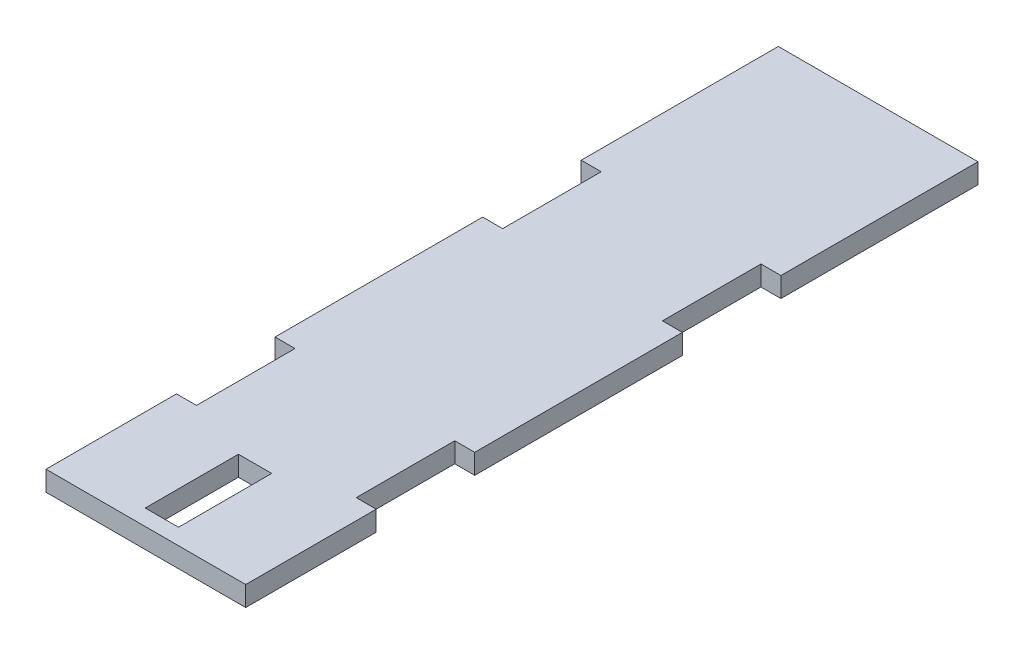
SolidWorks part; units mm, degrees
ref_plane "Спереди" through (0, 0, 0) normal (0, 0, 1) x (1, 0, 0)
ref_plane "Сверху" through (0, 0, 0) normal (0, 1, 0) x (1, 0, 0)
ref_plane "Справа" through (0, 0, 0) normal (1, 0, 0) x (0, 0, -1)
other "Configuration Table"
sketch "Эскиз1" plane through (0, 0, 0) normal (0, 1, 0) x (1, 0, 0)
  line L0 (-8.7681, 0) -> (8.7681, 0) construction
  line L1 (-15, -50) -> (15, -50)
  line L2 (-15, -50) -> (-15, -30.3972)
  line L3 (-15, 50) -> (15, 50)
  line L4 (15, -50) -> (15, -30.3972)
  line L5 (-15, -50) -> (15, 50) construction
  line L6 (-15, 50) -> (15, -50) construction
  line L7 (-15, 30.3972) -> (-12, 30.3972)
  line L9 (-15, 15.5972) -> (-12, 15.5972)
  line L10 (-12, 30.3972) -> (-12, 15.5972)
  line L11 (0, -13.162) -> (0, 13.162) construction
  line L12 (12, 30.3972) -> (12, 15.5972)
  line L13 (15, 15.5972) -> (12, 15.5972)
  line L15 (15, 30.3972) -> (12, 30.3972)
  line L16 (15, -30.3972) -> (12, -30.3972)
  line L18 (15, -15.5972) -> (12, -15.5972)
  line L19 (12, -30.3972) -> (12, -15.5972)
  line L20 (-12, -30.3972) -> (-12, -15.5972)
  line L21 (-15, -15.5972) -> (-12, -15.5972)
  line L23 (-15, -30.3972) -> (-12, -30.3972)
  line L24 (-15, 30.3972) -> (-15, 50)
  line L25 (15, 30.3972) -> (15, 50)
  line L26 (15, -15.5972) -> (15, 15.5972)
  line L27 (-15, -15.5972) -> (-15, 15.5972)
  point P0 (0, 0)
  point P13 (0, 0)
  point P16 (0, 0)
  dimension "D1" = 100
  dimension "D2" = 30
  dimension "D3" = 14.8
  dimension "D4" = 3
extrude "Бобышка-Вытянуть1" add sketch "Эскиз1" along normal blind 3
sketch "Эскиз2" plane through (0, 0, -50) normal (0, 0, -1) x (-1, 0, 0)
  line L4 (-15, 0) -> (15, 0)
  line L5 (15, 0) -> (15, 3)
  line L6 (15, 3) -> (-15, 3)
  line L7 (-15, 3) -> (-15, 0)
  line L8 (-15, 0) -> (15, 0)
  line L9 (15, 0) -> (15, 3)
  line L10 (15, 3) -> (-15, 3)
  line L11 (-15, 3) -> (-15, 0)
  dimension "D1" = 0
extrude "Бобышка-Вытянуть2" add sketch "Эскиз2" along normal blind 10
sketch "Эскиз4" plane through (0, 3, 0) normal (0, 1, 0) x (1, 0, 0)
  line L0 (12, -15.5972) -> (15, -15.5972) construction
  line L1 (-2.5, -47.5972) -> (2.5, -47.5972)
  line L2 (-2.5, -47.5972) -> (-2.5, -33.5972)
  line L3 (-2.5, -33.5972) -> (2.5, -33.5972)
  line L4 (2.5, -47.5972) -> (2.5, -33.5972)
  line L5 (15, -50) -> (15, -30.3972) construction
  dimension "D1" = 18
  dimension "D2" = 32
  dimension "D3" = 5
  dimension "D4" = 12.5
extrude "Вырез-Вытянуть1" cut sketch "Эскиз4" against normal blind 10
